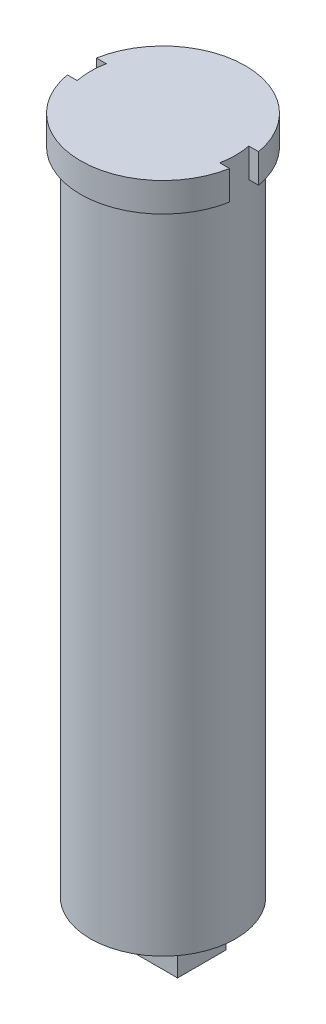
SolidWorks part; units mm, degrees
ref_plane "Front Plane" through (0, 0, 0) normal (0, 0, 1) x (1, 0, 0)
ref_plane "Top Plane" through (0, 0, 0) normal (0, 1, 0) x (1, 0, 0)
ref_plane "Right Plane" through (0, 0, 0) normal (1, 0, 0) x (0, 0, -1)
sketch "Sketch1" plane through (0, 0, 0) normal (0, 1, 0) x (1, 0, 0)
  line L0 (0, 0) -> (0, 15.0106) construction
  line L2 (-15.9423, 0) -> (14.9071, 0) construction
  line L8 (-8.3666, 1.5) -> (-7.3485, 1.5)
  line L9 (-8.3666, -1.5) -> (-7.3485, -1.5)
  line L10 (7.3485, 1.5) -> (8.3666, 1.5)
  line L11 (7.3485, -1.5) -> (8.3666, -1.5)
  arc A0 (-8.3666, -1.5) -> (8.3666, -1.5) centre (0, 0) ccw
  arc A2 (8.3666, 1.5) -> (-8.3666, 1.5) centre (0, 0) ccw
  arc A3 (-7.3485, 1.5) -> (-7.3485, -1.5) centre (0, 0) ccw
  arc A4 (7.3485, -1.5) -> (7.3485, 1.5) centre (0, 0) ccw
  point P10 (-7.3666, 0)
  dimension "D1" = 17
  dimension "D4" = 15
  dimension "D2" = 3
extrude "Boss-Extrude1" add sketch "Sketch1" along normal blind 3
sketch "Sketch2" plane through (0, 0, 0) normal (0, 1, 0) x (1, 0, 0)
  circle A0 centre (0, 0) radius 7.5
  dimension "D1" = 15
extrude "Boss-Extrude2" add sketch "Sketch2" against normal blind 67
sketch "Sketch4" plane through (0, -67, 0) normal (0, -1, 0) x (1, 0, 0)
  line L0 (-4, -2.5) -> (-4, 2.5)
  line L1 (12.2092, 0) -> (-9.7018, 0) construction
  line L2 (-4, 2.5) -> (4, 2.5)
  line L3 (0, 8.7527) -> (0, -9.4791) construction
  line L4 (4, -2.5) -> (4, 2.5)
  line L5 (-4, -2.5) -> (4, -2.5)
  circle A0 centre (0, 0) radius 7.5
  point P11 (0, 2.5)
  point P13 (4, 0)
  point P14 (-4, 0)
  dimension "D1" = 15
  dimension "D2" = 5
  dimension "D3" = 8
extrude "Boss-Extrude4" add sketch "Sketch4" along normal blind 4 contours L0 L5 L4 L2
sketch "Sketch5" plane through (0, 0, 0) normal (1, 0, 0) x (0, 0, -1)
  line L0 (-7.5, -67) -> (-7.5, 0) construction
  line L1 (-7.5, 0) -> (7.5, 0) construction
  line L2 (7.5, 0) -> (7.5, -67) construction
  line L3 (7.5, -67) -> (-7.5, -67) construction
  line L4 (-7.5, -51) -> (-3.5, -45)
  line L5 (-3.5, -45) -> (-3.5, -44)
  line L6 (-3.5, -44) -> (-7.5, -44)
  line L7 (7.5, -62) -> (3.5, -62)
  line L8 (3.5, -62) -> (3.5, -61)
  line L9 (3.5, -61) -> (7.5, -56)
  line L10 (7.5, -62) -> (7.5, -56)
  line L11 (-7.5, -44) -> (-7.5, -51)
  dimension "D1" = 16
  dimension "D2" = 1
  dimension "D3" = 23
  dimension "D4" = 4
  dimension "D5" = 5
  dimension "D6" = 11
  dimension "D7" = 4
  dimension "D8" = 1
extrude "Cut-Extrude1" cut sketch "Sketch5" against normal through all both and the other way through all
sketch "Sketch6" plane through (0, -67, 0) normal (0, -1, 0) x (-1, 0, 0)
  circle A0 centre (0, 0) radius 7.5
extrude "Boss-Extrude5" add sketch "Sketch6" against normal blind 30
